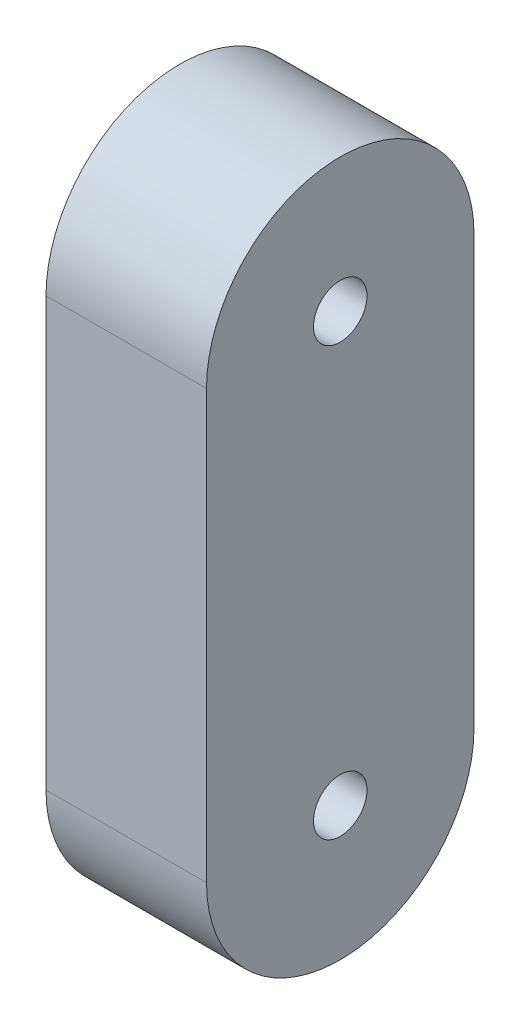
SolidWorks part; units mm, degrees
ref_plane "Front Plane" through (0, 0, 0) normal (0, 0, 1) x (1, 0, 0)
ref_plane "Top Plane" through (0, 0, 0) normal (0, 1, 0) x (1, 0, 0)
ref_plane "Right Plane" through (0, 0, 0) normal (1, 0, 0) x (0, 0, -1)
sketch "Sketch1" plane through (0, 0, 0) normal (1, 0, 0) x (0, 0, -1)
  line L2 (-25, 40) -> (-25, -40)
  line L4 (25, 40) -> (25, -40)
  line L5 (-25, 40) -> (25, -40) construction
  line L6 (-25, -40) -> (25, 40) construction
  arc A0 (-25, 40) -> (25, 40) centre (0, 40) cw
  arc A1 (-25, -40) -> (25, -40) centre (0, -40) ccw
  point P0 (0, 0)
  dimension "D1" = 80
  dimension "D2" = 50
extrude "Boss-Extrude1" add sketch "Sketch1" along normal blind 30
sketch "Sketch2" plane through (30, 0, 0) normal (1, 0, 0) x (0, 0, -1)
  circle A0 centre (0, 40) radius 5
  circle A1 centre (0, -40) radius 5
  dimension "D1" = 10
  dimension "D2" = 10
extrude "Cut-Extrude1" cut sketch "Sketch2" against normal blind 30
